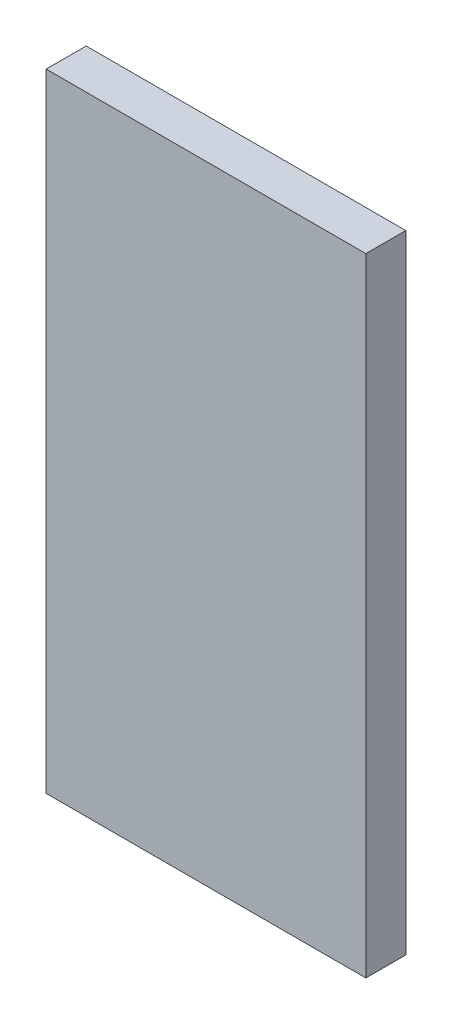
SolidWorks part; units mm, degrees
material "ABS PC"
ref_plane "X-Y Datum" through (0, 0, 0) normal (0, 0, 1) x (1, 0, 0)
ref_plane "X-Z Datum" through (0, 0, 0) normal (0, 1, 0) x (1, 0, 0)
ref_plane "Y-Z Datum" through (0, 0, 0) normal (1, 0, 0) x (0, 0, -1)
sketch "Sketch1" plane through (0, 0, 0) normal (0, 0, 1) x (1, 0, 0)
  line L1 (-25.4, -49.85) -> (25.4, -49.85)
  line L2 (-25.4, -49.85) -> (-25.4, 49.85)
  line L3 (-25.4, 49.85) -> (25.4, 49.85)
  line L4 (25.4, -49.85) -> (25.4, 49.85)
  line L5 (-25.4, -49.85) -> (25.4, 49.85) construction
  line L6 (-25.4, 49.85) -> (25.4, -49.85) construction
  point P0 (0, 0)
  dimension "D1" = 99.7001
  dimension "D2" = 50.8
extrude "Boss-Extrude1" add sketch "Sketch1" along normal blind 6.35
